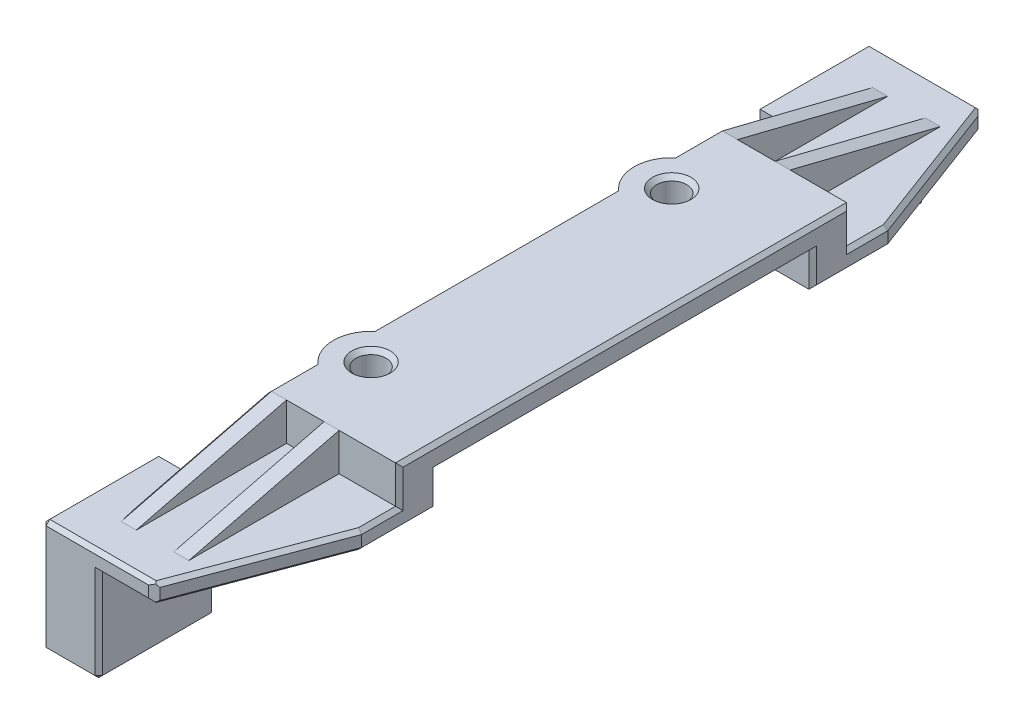
SolidWorks part; units mm, degrees
material "镁合金"
ref_plane "前视基准面" through (0, 0, 0) normal (0, 0, 1) x (1, 0, 0)
ref_plane "上视基准面" through (0, 0, 0) normal (0, 1, 0) x (1, 0, 0)
ref_plane "右视基准面" through (0, 0, 0) normal (1, 0, 0) x (0, 0, -1)
sketch "草图1" plane through (0, 0, 0) normal (0, 1, 0) x (1, 0, 0)
  line L1 (-3.5, 22) -> (3.5, 22)
  line L2 (-3.5, 22) -> (-3.5, -22)
  line L3 (-3.5, -22) -> (3.5, -22)
  line L4 (3.5, 22) -> (3.5, -22)
  line L5 (-3.5, 22) -> (3.5, -22) construction
  line L6 (-3.5, -22) -> (3.5, 22) construction
  point P0 (0, 0)
  dimension "D1" = 44
  dimension "D2" = 7
extrude "凸台-拉伸1" add sketch "草图1" along normal blind 3 contours L2 L3 L4 L1
sketch "草图2" plane through (0, 3, 0) normal (0, 1, 0) x (1, 0, 0)
  line L0 (3.5, 22) -> (0.5, 22)
  line L1 (-3.5, 22) -> (3.5, 22) construction
  line L2 (0.5, 22) -> (3.5, 14)
  line L3 (3.5, 22) -> (3.5, -22) construction
  line L4 (3.5, 14) -> (3.5, 22)
  line L5 (3.5, -22) -> (0.5, -22)
  line L6 (0.5, -22) -> (3.5, -14)
  line L7 (3.5, -14) -> (3.5, -22)
  dimension "D1" = 8
  dimension "D2" = 3
  dimension "D3" = 8
  dimension "D4" = 3
extrude "切除-拉伸1" cut sketch "草图2" against normal through all
sketch "草图3" plane through (3.5, 0, 0) normal (1, 0, 0) x (0, 0, -1)
  line L0 (-12, 3) -> (-22, 3)
  line L2 (14, 3) -> (-14, 3) construction
  line L3 (-22, 3) -> (-22, 1)
  line L4 (-22, 0) -> (-22, 3) construction
  line L5 (-22, 1) -> (-12, 3)
  line L6 (22, 3) -> (12, 3)
  line L7 (12, 3) -> (22, 1)
  line L8 (22, 0) -> (22, 3) construction
  line L9 (22, 1) -> (22, 3)
  line L11 (-22, 3) -> (-12, 3)
  line L12 (-22, 3) -> (-22, 1)
  line L13 (-22, 1) -> (-12, 1)
  line L14 (-12, 3) -> (-12, 1)
  line L15 (22, 3) -> (12, 3)
  line L16 (22, 3) -> (22, 1)
  line L17 (22, 1) -> (12, 1)
  line L18 (12, 3) -> (12, 1)
  line M5 (-14, 3) -> (-14, 0)
  line M7 (14, 0) -> (14, 3)
  line M8 (14, 3) -> (-14, 3)
  dimension "D1" = 10
  dimension "D2" = 2
  dimension "D3" = 10
  dimension "D4" = 2
extrude "切除-拉伸2" cut sketch "草图3" against normal through all contours L3 L5 L0 M5 | L5 L13 M5 | L14 L5 L13 M5 | L5 M5 M8 | L7 L18 L17 M7 | L17 L7 M7 | L7 L9 L6 M7 | L7 M8 M7
sketch "草图4" plane through (-3.5, 0, 0) normal (-1, 0, 0) x (0, 0, 1)
  line L0 (12, 3) -> (20, 1)
  line L1 (22, 1) -> (12, 1) construction
  line L2 (12, 3) -> (12, 1) construction
  dimension "D1" = 8
rib "筋4" sketch "草图4" sketch "草图4" thickness 1 extrusion direction parallel to sketch draft on no parameters "D1"=1
ref_plane "基准面1" through (-0.5, 0, 0) normal (-1, 0, 0) x (0, 0, 1)
sketch "草图5" plane through (-0.5, 0, 0) normal (-1, 0, 0) x (0, 0, 1)
  line L0 (12, 3) -> (20, 1) construction
  line L1 (12, 3) -> (20, 1)
rib "筋5" sketch "草图5" sketch "草图5" thickness 0.8 extrusion direction parallel to sketch draft on no parameters "D1"=0.8
sketch "草图10" plane through (-3.5, 0, 0) normal (-1, 0, 0) x (0, 0, 1)
  line L1 (-10, -1.8) -> (10, -1.8)
  line L2 (-10, -1.8) -> (-10, 1.8)
  line L3 (-10, 1.8) -> (10, 1.8)
  line L4 (10, -1.8) -> (10, 1.8)
  line L5 (-10, -1.8) -> (10, 1.8) construction
  line L6 (-10, 1.8) -> (10, -1.8) construction
  point P0 (0, 0)
  dimension "D1" = 20
  dimension "D2" = 3.6
extrude "切除-拉伸3" cut sketch "草图10" against normal through all
sketch "草图6" plane through (0, 3, 0) normal (0, 1, 0) x (1, 0, 0)
  line L0 (-3.5, -22) -> (0.5, -22) construction
  line L1 (-3.5, 12) -> (-3.5, -12) construction
  line L3 (-4, -6) -> (0, -6)
  line L4 (-4, -6) -> (-4, -10)
  line L5 (-4, -10) -> (0, -10)
  line L6 (0, -6) -> (0, -10)
  line L7 (-4, -6) -> (0, -10) construction
  line L8 (-4, -10) -> (0, -6) construction
  circle A0 centre (-2, -8) radius 2
  line M6 (-3.5, 12) -> (-3.5, -12)
  dimension "D1" = 4
  dimension "D2" = 14
  dimension "D3" = 1.5
  dimension "D4" = 4
  dimension "D5" = 4
extrude "凸台-拉伸2" add sketch "草图6" against normal blind 3 contours A0 M6 | L5 A0 L3 M6 | A0 L5 L6 | A0 L6 L3
hole_wizard "M2 螺纹孔1" positions "草图7" profile "草图8" tap size "M2" standard "GB"
sketch "草图7" plane through (0, 3, 0) normal (0, 1, 0) x (1, 0, 0)
  point P0 (-2, -8)
sketch "草图8" plane through (-2, 3, 8) normal (1, 0, 0) x (0, 0, 1)
  line L0 (0, 0) -> (0, 6.4807)
  line L1 (0, 6.4807) -> (0.8, 6)
  line L2 (0.8, 6) -> (0.8, 0.225)
  line L3 (0.8, 0.225) -> (1.025, 0)
  line L5 (1.025, 0) -> (0, 0)
  line L6 (-0.8, 0.225) -> (-1.025, 0) construction
  line L10 (0, 6.4807) -> (-0.8, 6) construction
  line L11 (0, -6.35) -> (0, 107.95) construction
  dimension "螺纹孔钻头直径" = 1.6
  dimension "螺纹孔钻头深度" = 6
  dimension "近端锥形沉头孔直径" = 2.05
  dimension "近端锥形沉头孔角度" = 90
  dimension "导头角度" = 118
cosmetic thread "孔螺蚊线1" parameters "D1"=3, "D2"=2
sketch "草图9" plane through (-3.5, 0, 0) normal (-1, 0, 0) x (0, 0, 1)
  line L1 (22, 1) -> (16, 1)
  line L2 (22, 1) -> (22, -5)
  line L3 (22, -5) -> (16, -5)
  line L4 (16, 1) -> (16, -5)
  dimension "D1" = 6
  dimension "D2" = 6
extrude "凸台-拉伸3" add sketch "草图9" along normal blind 2 and the other way blind 1
mirror "镜向1" about plane through (0, 0, 0) normal (0, 0, 1) of "M2 螺纹孔1", "凸台-拉伸2", "凸台-拉伸3", "筋5", "筋4"
chamfer "倒角1" distance 0.2 angle 45 22 edges at (0.5, 0.5, -22) (-1, 0, 22) (-2.5, -2.5, 22) (-4, -5, 22) (-2.5, -5, 19) (-4, -5, 16) (-5.5, -2, 22) (-5.5, 1, 19) (-5.5, -2, 16) (-5.5, -5, 19) (0.5, 0.5, 22) (-1, 0, -22) (-4, -5, -22) (-5.5, -2, -22) (-5.5, -2, -16) (-5.5, 1, -19) (-4, -5, -16) (-5.5, -5, -19) (-2.5, -2.5, -22) (-2.5, -5, -19) (-2.5, 1, 22) (-2.5, 1, -22)
chamfer "倒角2" distance 0.2 angle 45 14 edges at (2.06, 0, -17.84) (2.06, 1, -17.84) (3.5, 0, -12) (3.5, 0.9, -10) (3.5, 1.8, 0) (3.5, 0.9, 10) (3.5, 0, 12) (2.0375, 0, 17.9) (3.5, 1, -13) (3.5, 2, -12) (3.5, 3, 0) (3.5, 2, 12) (3.5, 1, 13) (2.0375, 1, 17.9)
chamfer "倒角3" distance 0.2 angle 45 8 edges at (-3.5, 0, 13) (-3.5, 1.8, 0) (-3.5, 3, 10.6614) (-3.5, 2, -16) (-3.5, 3, 0) (-3.5, 0, -13) (-3.5, 3, -10.6614) (-3.5, 2, 16)
